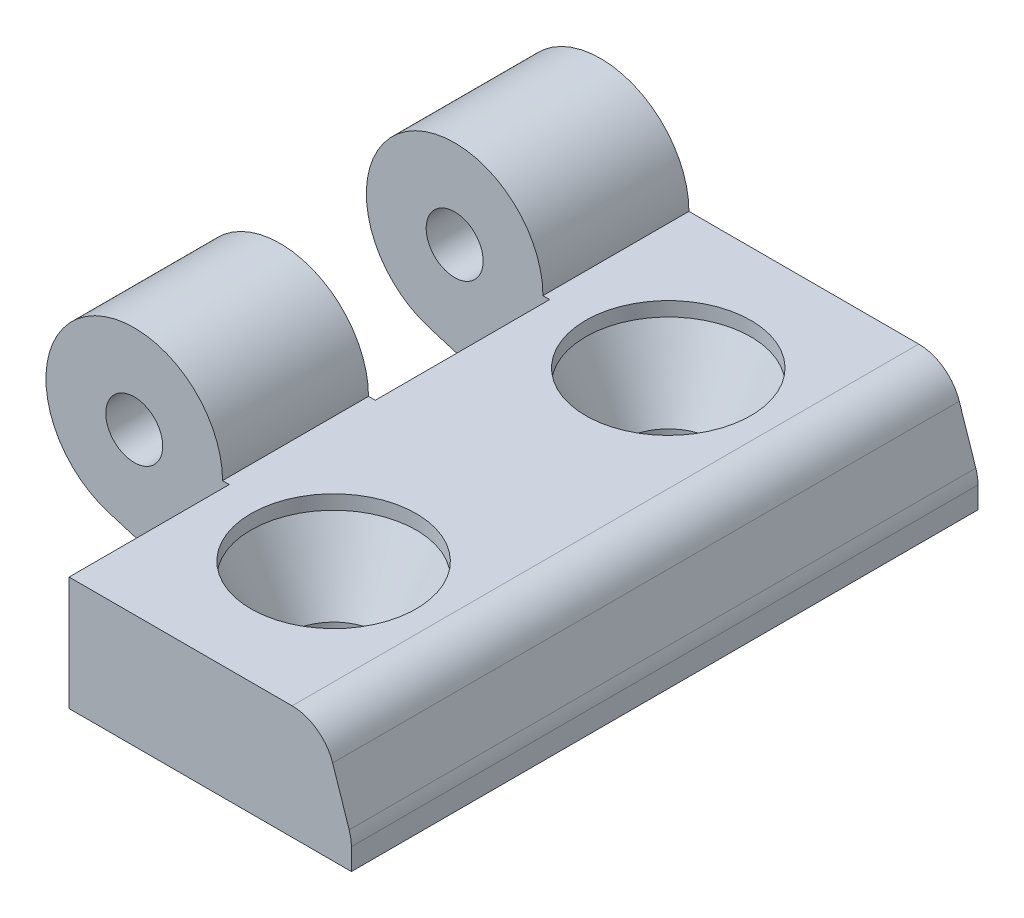
SolidWorks part; units mm, degrees
ref_plane "前视基准面" through (0, 0, 0) normal (0, 0, 1) x (1, 0, 0)
ref_plane "上视基准面" through (0, 0, 0) normal (0, 1, 0) x (1, 0, 0)
ref_plane "右视基准面" through (0, 0, 0) normal (1, 0, 0) x (0, 0, -1)
sketch "草图1" plane through (0, 0, 0) normal (0, 0, 1) x (1, 0, 0)
  line B0 (26.5, -8) -> (26.5, -6.4868)
  line B1 (6.2, 0) -> (22.3377, 0)
  line B2 (5, -8) -> (26.5, -8)
  line B3 (5, -8) -> (-1.8032, -5.932)
  line B4 (26.346, -5.5381) -> (25.1838, -2.0513)
  arc B5 (25.1838, -2.0513) -> (22.3377, 0) centre (22.3377, -3) ccw
  arc B6 (6.2, 0) -> (-1.8032, -5.932) centre (0, 0) ccw
  arc B7 (26.5, -6.4868) -> (26.346, -5.5381) centre (23.5, -6.4868) ccw
sketch_block_instance "A$C3A447B15-1"
sketch_block "A$C3A447B15"
extrude "凸台-拉伸1" add sketch "草图1" along normal mid plane 44
sketch "草图3" plane through (0, 0, 0) normal (0, 1, 0) x (1, 0, 0)
  line L1 (6.6744, -22) -> (-9.0362, -22)
  line L2 (6.6744, -22) -> (6.6744, -10.75)
  line L3 (6.6744, -10.75) -> (-9.0362, -10.75)
  line L4 (-9.0362, -22) -> (-9.0362, -10.75)
  line L5 (26.5, 0) -> (36.0417, 0) construction
  line L6 (6.6744, -0.5) -> (-10.336, -0.5)
  line L7 (6.6744, -0.5) -> (6.6744, 11.75)
  line L8 (6.6744, 11.75) -> (-10.336, 11.75)
  line L9 (-10.336, -0.5) -> (-10.336, 11.75)
  line L10 (26.5, -22) -> (26.5, 22) construction
extrude "切除-拉伸1" cut sketch "草图3" against normal through all and the other way through all
sketch "草图4" plane through (0, 0, -22) normal (0, 0, -1) x (-1, 0, 0)
  circle A0 centre (0, 0) radius 2
extrude "切除-拉伸2" cut sketch "草图4" against normal through all
ref_plane "基准面2" through (0, 0, -11.75) normal (0, 0, -1) x (-1, 0, 0)
sketch "草图5" plane through (0, 0, -11.75) normal (0, 0, -1) x (-1, 0, 0)
  line L0 (-15, 0) -> (-15, -8)
  line L1 (-22.3377, 0) -> (-6.2, 0) construction
  line L2 (-5, -8) -> (-26.5, -8) construction
  line L3 (-11.75, -8) -> (-11.75, -6)
  line L4 (-9.2, 0) -> (-9.2, -1)
  line L5 (-9.2, -1) -> (-11.75, -6)
  line L6 (-15, -8) -> (-11.75, -8)
  line L7 (-15, 0) -> (-9.2, 0)
  circle A0 centre (0, 0) radius 2 construction
  dimension "D1" = 15
  dimension "D2" = 3.25
  dimension "D3" = 2
  dimension "D4" = 5.8
  dimension "D5" = 1
revolve "切除-旋转1" cut sketch "草图5" angle 360 about L0
pattern_linear "阵列(线性)1" count 2 spacing 23.5 along (0, 0, 1) of "切除-旋转1"
